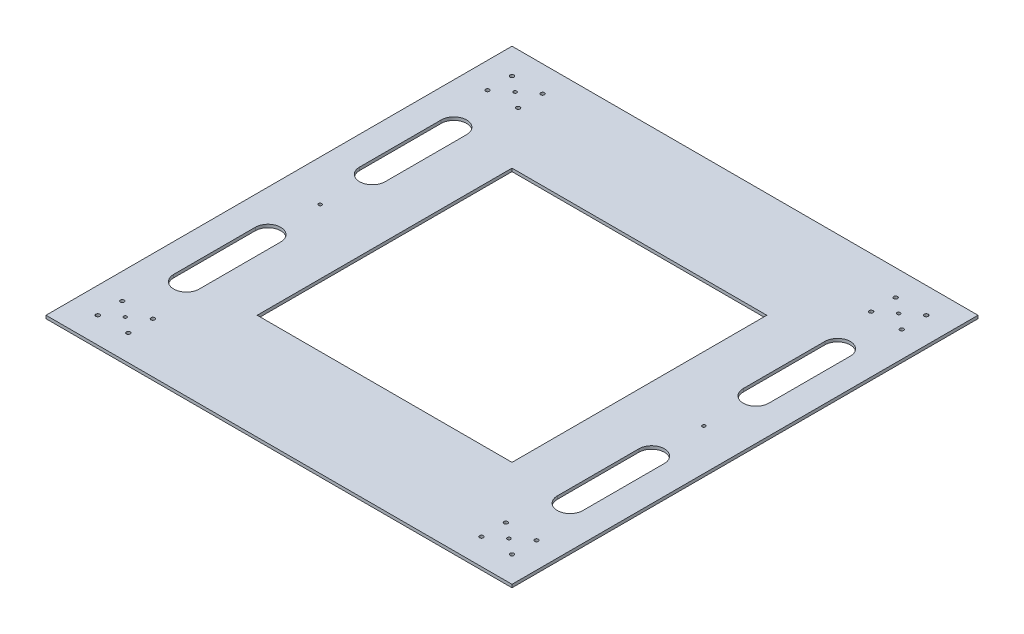
SolidWorks part; units mm, degrees
ref_plane "Front Plane" through (0, 0, 0) normal (0, 0, 1) x (1, 0, 0)
ref_plane "Top Plane" through (0, 0, 0) normal (0, 1, 0) x (1, 0, 0)
ref_plane "Right Plane" through (0, 0, 0) normal (1, 0, 0) x (0, 0, -1)
sketch "Sketch1" plane through (0, 0, 0) normal (0, 1, 0) x (1, 0, 0)
  line L1 (-228.6, 228.6) -> (228.6, 228.6)
  line L2 (-228.6, 228.6) -> (-228.6, -228.6)
  line L3 (-228.6, -228.6) -> (228.6, -228.6)
  line L4 (228.6, 228.6) -> (228.6, -228.6)
  line L5 (-228.6, 228.6) -> (228.6, -228.6) construction
  line L6 (-228.6, -228.6) -> (228.6, 228.6) construction
  point P0 (0, 0)
  dimension "D1" = 457.2
  dimension "D2" = 457.2
extrude "Boss-Extrude1" add sketch "Sketch1" along normal blind 3
sketch "Sketch2" plane through (0, 3, 0) normal (0, 1, 0) x (1, 0, 0)
  line L0 (-203.2, 203.2) -> (-173.2, 203.2) construction
  line L5 (0, 203.2) -> (0, 0) construction
  line L6 (0, 0) -> (-203.2, 0) construction
  line L8 (203.2, -203.2) -> (203.2, 203.2)
  line L9 (203.2, 203.2) -> (-203.2, 203.2)
  line L10 (-203.2, 203.2) -> (-203.2, -203.2)
  line L11 (-203.2, -203.2) -> (203.2, -203.2)
  line L12 (203.2, -203.2) -> (203.2, 203.2)
  line L13 (203.2, 203.2) -> (-203.2, 203.2)
  line L14 (-203.2, 203.2) -> (-203.2, -203.2)
  line L15 (-203.2, -203.2) -> (203.2, -203.2)
  circle A1 centre (-173.2, 203.2) radius 1.875
  circle A2 centre (173.2, 203.2) radius 1.875
  circle A7 centre (-173.2, -203.2) radius 1.875
  circle A8 centre (-203.2, 203.2) radius 1.875
  circle A9 centre (-203.2, 179.2) radius 1.875
  circle A10 centre (-173.2, 179.2) radius 1.875
  circle A11 centre (-173.2, -203.2) radius 1.875
  circle A12 centre (-173.2, -179.2) radius 1.875
  circle A13 centre (-203.2, -179.2) radius 1.875
  circle A14 centre (-203.2, -203.2) radius 1.875
  circle A15 centre (173.2, 203.2) radius 1.875
  circle A16 centre (173.2, 179.2) radius 1.875
  circle A17 centre (203.2, 179.2) radius 1.875
  circle A18 centre (203.2, 203.2) radius 1.875
  circle A19 centre (203.2, -203.2) radius 1.875
  circle A20 centre (203.2, -179.2) radius 1.875
  circle A21 centre (173.2, -179.2) radius 1.875
  circle A22 centre (173.2, -203.2) radius 1.875
  circle A23 centre (173.2, -203.2) radius 1.875
  dimension "D2" = 24
  dimension "D4" = 30
  dimension "D5" = 3.75
  dimension "D3" = 30
  dimension "D6" = 24
  dimension "D1" = 25.4
extrude "Cut-Extrude2" cut sketch "Sketch2" against normal through all contours A8 | A9 | A10 | A1 | A2 | A16 | A18 | A17 | A20 | A19 | A22 | A21 | A14 | A13 | A12 | A7
sketch "Sketch3" plane through (0, 3, 0) normal (0, 1, 0) x (1, 0, 0)
  line L0 (-203.2, 203.2) -> (-173.2, 203.2) construction
  line L1 (-203.2, 203.2) -> (-203.2, 179.2) construction
  line L2 (-203.2, 179.2) -> (-173.2, 179.2) construction
  line L3 (-173.2, 179.2) -> (-173.2, 203.2) construction
  line L4 (0, 0) -> (0, 228.6) construction
  line L5 (228.6, 228.6) -> (-228.6, 228.6) construction
  line L6 (0, 0) -> (-228.6, 0) construction
  line L7 (-228.6, 228.6) -> (-228.6, -228.6) construction
  circle A0 centre (-188.2, 191.2) radius 1.625
  circle A1 centre (-188.2, -191.2) radius 1.625
  circle A2 centre (188.2, 191.2) radius 1.625
  circle A3 centre (188.2, -191.2) radius 1.625
  circle A4 centre (-188.2, 0) radius 1.625
  circle A5 centre (188.2, 0) radius 1.625
  point P10 (-188.2, 203.2)
  point P11 (-203.2, 191.2)
  point P28 (0, 0)
  dimension "D1" = 3.25
extrude "Cut-Extrude3" cut sketch "Sketch3" against normal through all
sketch "Sketch4" plane through (0, 3, 0) normal (0, 1, 0) x (1, 0, 0)
  line L0 (-188.2, 191.2) -> (-188.2, 131.2) construction
  line L1 (0, 0) -> (-228.6, 0) construction
  line L2 (0, 0) -> (0, 228.6) construction
  line L3 (228.6, 228.6) -> (-228.6, 228.6) construction
  line L4 (-228.6, 228.6) -> (-228.6, -228.6) construction
  line L5 (-200.7, 131.2) -> (-200.7, 51.2)
  line L6 (-175.7, 131.2) -> (-175.7, 51.2)
  line L7 (-175.7, -131.2) -> (-175.7, -51.2)
  line L8 (-200.7, -131.2) -> (-200.7, -51.2)
  line L9 (200.7, -131.2) -> (200.7, -51.2)
  line L10 (175.7, -131.2) -> (175.7, -51.2)
  line L11 (175.7, 131.2) -> (175.7, 51.2)
  line L12 (200.7, 131.2) -> (200.7, 51.2)
  arc A0 (-175.7, 131.2) -> (-200.7, 131.2) centre (-188.2, 131.2) ccw
  circle A1 centre (-188.2, 191.2) radius 1.625 construction
  arc A3 (-200.7, 51.2) -> (-175.7, 51.2) centre (-188.2, 51.2) ccw
  arc A4 (-200.7, -51.2) -> (-175.7, -51.2) centre (-188.2, -51.2) cw
  arc A5 (-175.7, -131.2) -> (-200.7, -131.2) centre (-188.2, -131.2) cw
  arc A6 (175.7, -131.2) -> (200.7, -131.2) centre (188.2, -131.2) ccw
  arc A7 (200.7, -51.2) -> (175.7, -51.2) centre (188.2, -51.2) ccw
  arc A8 (200.7, 51.2) -> (175.7, 51.2) centre (188.2, 51.2) cw
  arc A9 (175.7, 131.2) -> (200.7, 131.2) centre (188.2, 131.2) cw
  dimension "D1" = 60
  dimension "D2" = 25
  dimension "D5" = 25
  dimension "D6" = 80
extrude "Cut-Extrude4" cut sketch "Sketch4" against normal through all
sketch "Sketch5" plane through (0, 3, 0) normal (0, 1, 0) x (1, 0, 0)
  line L5 (-125, 125) -> (125, 125)
  line L6 (-125, 125) -> (-125, -125)
  line L7 (-125, -125) -> (125, -125)
  line L8 (125, 125) -> (125, -125)
  line L9 (-125, 125) -> (125, -125) construction
  line L10 (-125, -125) -> (125, 125) construction
  point P0 (0, 0)
  dimension "D1" = 250
  dimension "D2" = 250
extrude "Cut-Extrude5" cut sketch "Sketch5" against normal through all
